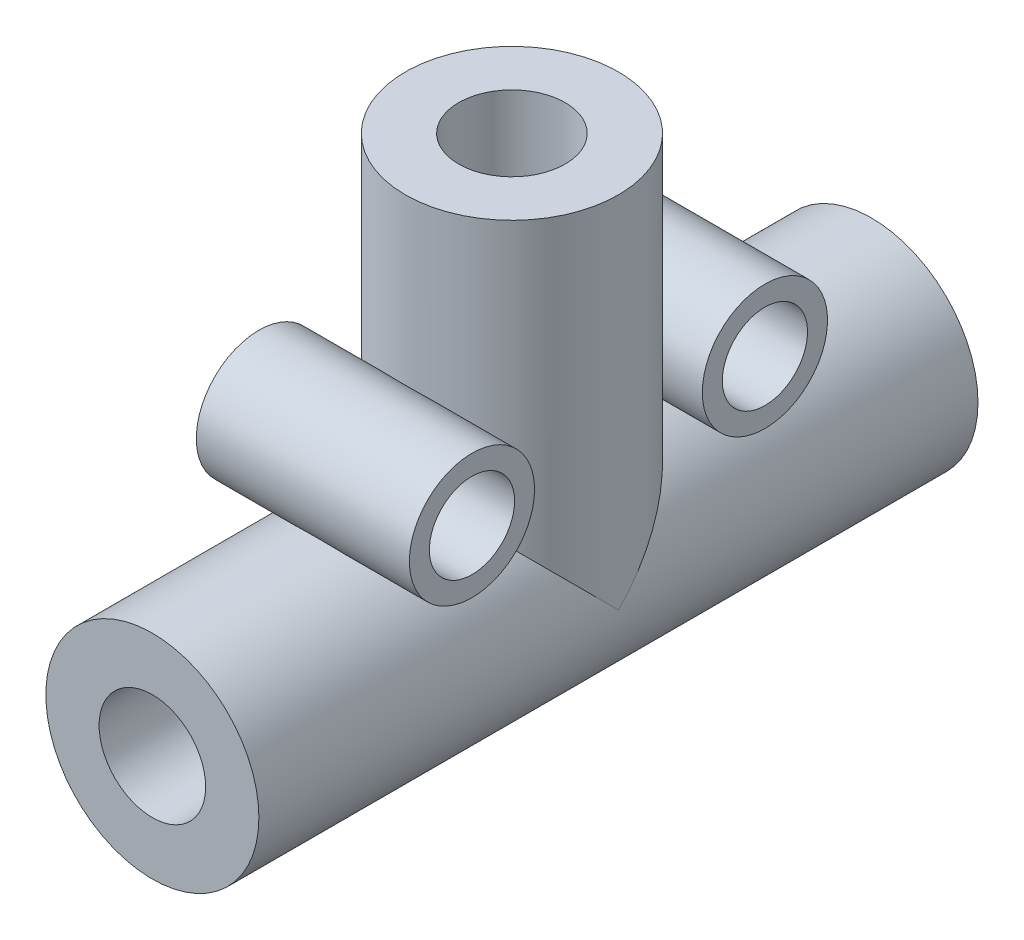
SolidWorks part; units mm, degrees
ref_plane "Plan de face" through (0, 0, 0) normal (0, 0, 1) x (1, 0, 0)
ref_plane "Plan de dessus" through (0, 0, 0) normal (0, 1, 0) x (1, 0, 0)
ref_plane "Plan de droite" through (0, 0, 0) normal (1, 0, 0) x (0, 0, -1)
sketch "Esquisse1" plane through (0, 0, 0) normal (0, 0, 1) x (1, 0, 0)
  circle A0 centre (0, 0) radius 4
  circle A1 centre (0, 0) radius 2
  dimension "D1" = 8
  dimension "D2" = 4
extrude "Boss.-Extru.1" add sketch "Esquisse1" along normal mid plane 27
sketch "Esquisse2" plane through (0, 0, 0) normal (0, 1, 0) x (1, 0, 0)
  circle A0 centre (0, 0) radius 4
  circle A1 centre (0, 0) radius 2
  dimension "D1" = 8
  dimension "D2" = 4
extrude "Boss.-Extru.2" add sketch "Esquisse2" against normal up to next from offset 13.5
sketch "Esquisse3" plane through (0, 0, 0) normal (1, 0, 0) x (0, 0, -1)
  line L0 (0, 0) -> (0, 2.815) construction
  circle A0 centre (-5.5, 5.5) radius 1.6
  circle A1 centre (-5.5, 5.5) radius 2.35
  circle A2 centre (5.5, 5.5) radius 2.35
  circle A3 centre (5.5, 5.5) radius 1.6
  dimension "D1" = 3.2
  dimension "D2" = 4.7
  dimension "D3" = 11
  dimension "D4" = 5.5
extrude "Boss.-Extru.3" add sketch "Esquisse3" along normal mid plane 8
